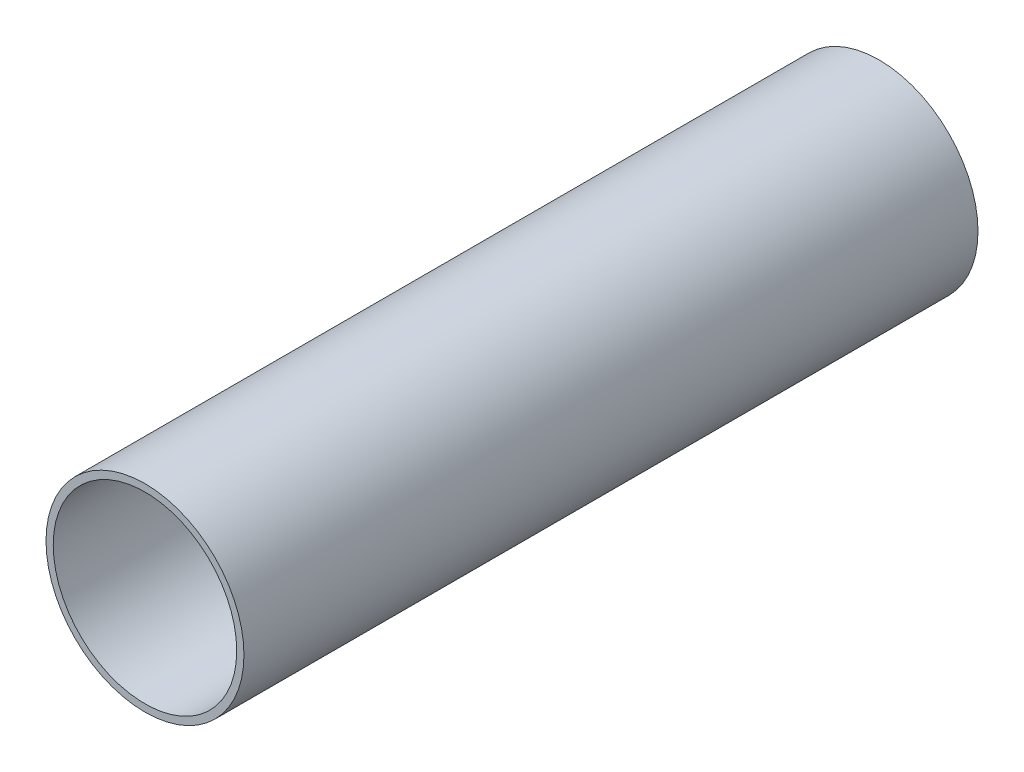
SolidWorks part; units mm, degrees
material "Acrylic (Medium-high impact)"
ref_plane "Front Plane" through (0, 0, 0) normal (0, 0, 1) x (1, 0, 0)
ref_plane "Top Plane" through (0, 0, 0) normal (0, 1, 0) x (1, 0, 0)
ref_plane "Right Plane" through (0, 0, 0) normal (1, 0, 0) x (0, 0, -1)
sketch "Sketch1" plane through (0, 0, 0) normal (0, 0, 1) x (1, 0, 0)
  circle A0 centre (0, 0) radius 50.8
  circle A1 centre (0, 0) radius 54.8
  dimension "D1" = 101.6
  dimension "D2" = 4
extrude "Boss-Extrude1" add sketch "Sketch1" along normal mid plane 406.4
